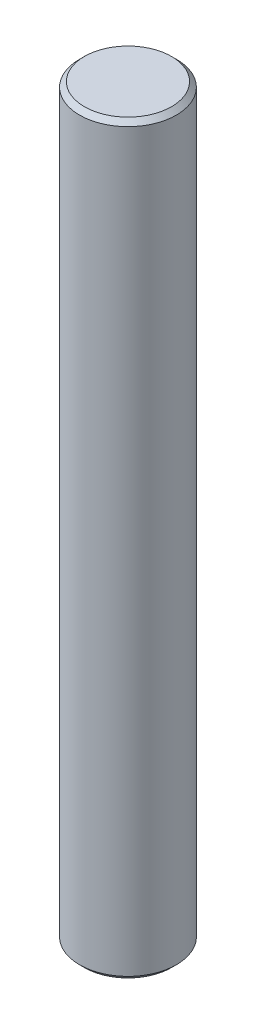
SolidWorks part; units mm, degrees
ref_plane "Front Plane" through (0, 0, 0) normal (0, 0, 1) x (1, 0, 0)
ref_plane "Top Plane" through (0, 0, 0) normal (0, 1, 0) x (1, 0, 0)
ref_plane "Right Plane" through (0, 0, 0) normal (1, 0, 0) x (0, 0, -1)
sketch "Sketch1" plane through (0, 0, 0) normal (0, 1, 0) x (1, 0, 0)
  circle A0 centre (0, 0) radius 12.7
  dimension "D1" = 25.4
extrude "Boss-Extrude1" add sketch "Sketch1" along normal blind 195.58
chamfer "Chamfer1" distance 1.27 angle 45 2 edges at (0, 195.58, 12.7) (0, 0, 12.7)
